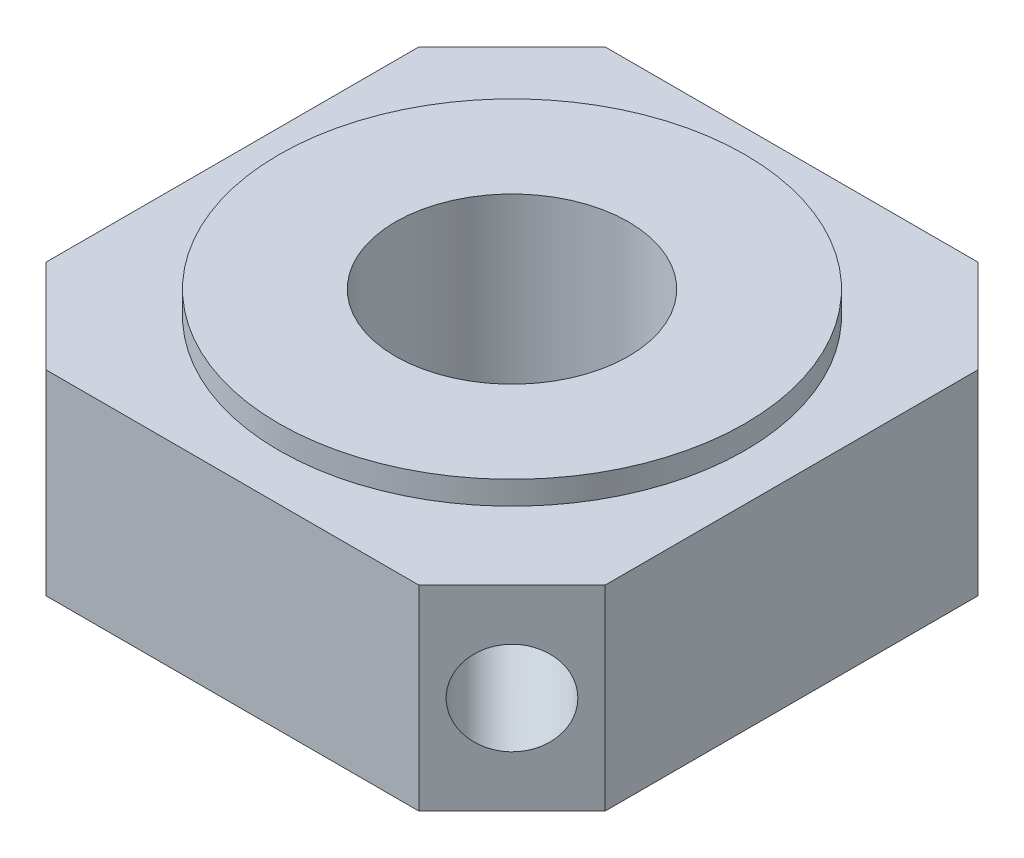
SolidWorks part; units mm, degrees
ref_plane "Front Plane" through (0, 0, 0) normal (0, 0, 1) x (1, 0, 0)
ref_plane "Top Plane" through (0, 0, 0) normal (0, 1, 0) x (1, 0, 0)
ref_plane "Right Plane" through (0, 0, 0) normal (1, 0, 0) x (0, 0, -1)
sketch "Sketch1" plane through (0, 0, 0) normal (0, 1, 0) x (1, 0, 0)
  line L0 (-4, 6) -> (-6, 4)
  line L1 (-4, -6) -> (4, -6)
  line L2 (-6, -4) -> (-6, 4)
  line L3 (-4, 6) -> (4, 6)
  line L4 (6, -4) -> (6, 4)
  line L5 (-5, -5) -> (5, 5) construction
  line L6 (-5, 5) -> (5, -5) construction
  line L7 (6, -4) -> (4, -6)
  line L8 (-6, -4) -> (-4, -6)
  line L9 (4, 6) -> (6, 4)
  point P0 (0, 0)
extrude "Boss-Extrude1" add sketch "Sketch1" along normal blind 4.2
sketch "Sketch3" plane through (0, 4.2, 0) normal (0, 1, 0) x (1, 0, 0)
  circle A0 centre (0, 0) radius 5
  dimension "D1" = 10
extrude "Boss-Extrude2" add sketch "Sketch3" along normal blind 0.5
sketch "Sketch4" plane through (0, 4.7, 0) normal (0, 1, 0) x (1, 0, 0)
  circle A0 centre (0, 0) radius 2.5
  dimension "D1" = 5
extrude "Cut-Extrude1" cut sketch "Sketch4" against normal up to next
sketch "Sketch5" plane through (5, 0, 5) normal (0.7071, 0, 0.7071) x (0.7071, 0, -0.7071)
  line L1 (-1.4142, 4.2) -> (-1.4142, 0) construction
  circle A0 centre (0, 2.1) radius 1
  point P6 (-1.4142, 2.1)
  dimension "D1" = 2
extrude "Cut-Extrude2" cut sketch "Sketch5" against normal up to next
